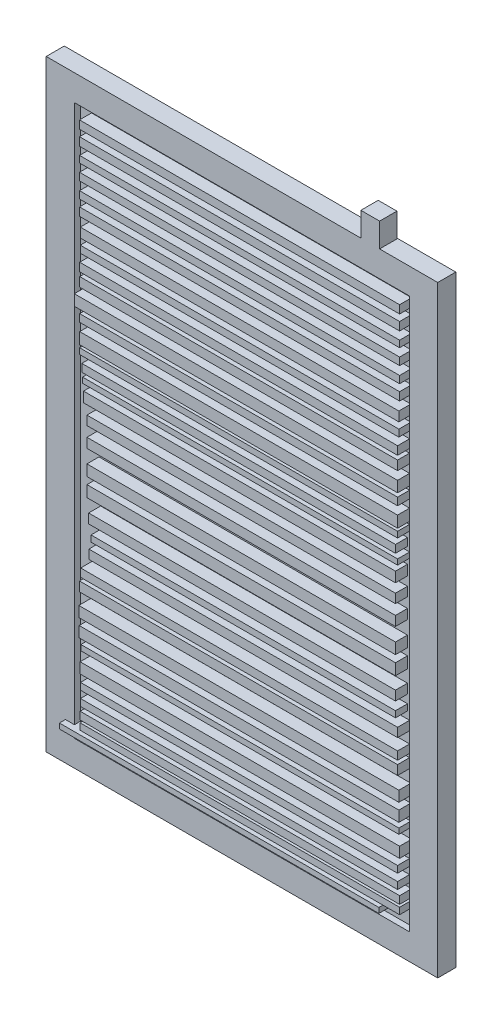
SolidWorks part; units mm, degrees
ref_plane "Front Plane" through (0, 0, 0) normal (0, 0, 1) x (1, 0, 0)
ref_plane "Top Plane" through (0, 0, 0) normal (0, 1, 0) x (1, 0, 0)
ref_plane "Right Plane" through (0, 0, 0) normal (1, 0, 0) x (0, 0, -1)
sketch "Sketch1" plane through (0, 0, 0) normal (0, 0, 1) x (1, 0, 0)
  line L1 (-32.5, 50) -> (32.5, 50)
  line L2 (-32.5, 50) -> (-32.5, -50)
  line L3 (-32.5, -50) -> (32.5, -50)
  line L4 (32.5, 50) -> (32.5, -50)
  point P0 (0, 0)
  point P6 (0, 0)
  dimension "D1" = 65
  dimension "D2" = 100
extrude "Boss-Extrude1" add sketch "Sketch1" along normal blind 3
sketch "Sketch2" plane through (0, 0, 0) normal (0, 0, -1) x (-1, 0, 0)
  line L1 (-27.7051, 45.4905) -> (27.7051, 45.4905)
  line L2 (-27.7051, 45.4905) -> (-27.7051, -45.4905)
  line L3 (-27.7051, -45.4905) -> (27.7051, -45.4905)
  line L4 (27.7051, 45.4905) -> (27.7051, -45.4905)
  line L5 (-27.7051, 45.4905) -> (27.7051, -45.4905) construction
  line L6 (-27.7051, -45.4905) -> (27.7051, 45.4905) construction
  point P0 (0, 0)
extrude "Cut-Extrude1" cut sketch "Sketch2" against normal blind 1
sketch "Sketch3" plane through (0, 0, 3) normal (0, 0, 1) x (1, 0, 0)
  line L1 (-27.8118, 45.7085) -> (27.8118, 45.7085)
  line L2 (-27.8118, 45.7085) -> (-27.8118, -45.7085)
  line L3 (-27.8118, -45.7085) -> (27.8118, -45.7085)
  line L4 (27.8118, 45.7085) -> (27.8118, -45.7085)
  line L5 (-27.8118, 45.7085) -> (27.8118, -45.7085) construction
  line L6 (-27.8118, -45.7085) -> (27.8118, 45.7085) construction
  point P0 (0, 0)
extrude "Cut-Extrude2" cut sketch "Sketch3" against normal blind 1
sketch "Sketch6" plane through (0, 50, 0) normal (0, 1, 0) x (1, 0, 0)
  line L0 (32.5, -3) -> (-32.5, -3) construction
  line L1 (19.7425, -0.1252) -> (22.8506, -0.1252)
  line L2 (19.7425, -0.1252) -> (19.7425, -3)
  line L3 (19.7425, -3) -> (22.8506, -3)
  line L4 (22.8506, -0.1252) -> (22.8506, -3)
  line L5 (19.7425, -0.1252) -> (22.8506, -3) construction
  line L6 (19.7425, -3) -> (22.8506, -0.1252) construction
  point P0 (21.2966, -1.5626)
extrude "Boss-Extrude3" add sketch "Sketch6" along normal blind 4
sketch "Sketch7" plane through (0, 0, 2) normal (0, 0, 1) x (1, 0, 0)
  line L1 (-25.9695, 44.6396) -> (27.1687, 44.6396)
  line L2 (-25.9695, 44.6396) -> (-25.9695, 43.2996)
  line L3 (-25.9695, 43.2996) -> (27.1687, 43.2996)
  line L4 (27.1687, 44.6396) -> (27.1687, 43.2996)
  line L5 (-25.9695, 44.6396) -> (27.1687, 43.2996) construction
  line L6 (-25.9695, 43.2996) -> (27.1687, 44.6396) construction
  line L7 (-25.9695, 42.2223) -> (27.1687, 42.2223)
  line L8 (-25.9695, 42.2223) -> (-25.9695, 40.8553)
  line L9 (-25.9695, 40.8553) -> (27.1687, 40.8553)
  line L10 (27.1687, 42.2223) -> (27.1687, 40.8553)
  line L11 (-25.9695, 42.2223) -> (27.1687, 40.8553) construction
  line L12 (-25.9695, 40.8553) -> (27.1687, 42.2223) construction
  line L13 (-25.9695, 39.5391) -> (27.1687, 39.5391)
  line L14 (-25.9695, 39.5391) -> (-25.9695, 38.446)
  line L15 (-25.9695, 38.446) -> (27.1687, 38.446)
  line L16 (27.1687, 39.5391) -> (27.1687, 38.446)
  line L17 (-25.9695, 39.5391) -> (27.1687, 38.446) construction
  line L18 (-25.9695, 38.446) -> (27.1687, 39.5391) construction
  line L19 (-25.9695, 37.1137) -> (27.1687, 37.1137)
  line L20 (-25.9695, 37.1137) -> (-25.9695, 35.8726)
  line L21 (-25.9695, 35.8726) -> (27.1687, 35.8726)
  line L22 (27.1687, 37.1137) -> (27.1687, 35.8726)
  line L23 (-25.9695, 37.1137) -> (27.1687, 35.8726) construction
  line L24 (-25.9695, 35.8726) -> (27.1687, 37.1137) construction
  line L25 (-25.9695, 34.4668) -> (27.1687, 34.4668)
  line L26 (-25.9695, 34.4668) -> (-25.9695, 33.2688)
  line L27 (-25.9695, 33.2688) -> (27.1687, 33.2688)
  line L28 (27.1687, 34.4668) -> (27.1687, 33.2688)
  line L29 (-25.9695, 34.4668) -> (27.1687, 33.2688) construction
  line L30 (-25.9695, 33.2688) -> (27.1687, 34.4668) construction
  line L31 (-25.9695, 32.1331) -> (27.1687, 32.1331)
  line L32 (-25.9695, 32.1331) -> (-25.9695, 30.7838)
  line L33 (-25.9695, 30.7838) -> (27.1687, 30.7838)
  line L34 (27.1687, 32.1331) -> (27.1687, 30.7838)
  line L35 (-25.9695, 32.1331) -> (27.1687, 30.7838) construction
  line L36 (-25.9695, 30.7838) -> (27.1687, 32.1331) construction
  line L37 (-25.8446, 29.2928) -> (27.0438, 29.2928)
  line L38 (-25.8446, 29.2928) -> (-25.8446, 27.7285)
  line L39 (-25.8446, 27.7285) -> (27.0438, 27.7285)
  line L40 (27.0438, 29.2928) -> (27.0438, 27.7285)
  line L41 (-25.8446, 29.2928) -> (27.0438, 27.7285) construction
  line L42 (-25.8446, 27.7285) -> (27.0438, 29.2928) construction
  line L43 (-25.8446, 25.535) -> (27.0438, 25.535)
  line L44 (-25.8446, 25.535) -> (-25.8446, 26.6899)
  line L45 (-25.8446, 26.6899) -> (27.0438, 26.6899)
  line L46 (27.0438, 25.535) -> (27.0438, 26.6899)
  line L47 (-25.8446, 25.535) -> (27.0438, 26.6899) construction
  line L48 (-25.8446, 26.6899) -> (27.0438, 25.535) construction
  line L49 (-25.9396, 22.8114) -> (26.8318, 22.8114)
  line L50 (-25.9396, 22.8114) -> (-25.9396, 24.1936)
  line L51 (-25.9396, 24.1936) -> (26.8318, 24.1936)
  line L52 (26.8318, 22.8114) -> (26.8318, 24.1936)
  line L53 (-25.9396, 22.8114) -> (26.8318, 24.1936) construction
  line L54 (-25.9396, 24.1936) -> (26.8318, 22.8114) construction
  line L55 (-25.9396, 22.1309) -> (26.8318, 22.1309)
  line L56 (-25.9396, 22.1309) -> (-25.9396, 20.6025)
  line L57 (-25.9396, 20.6025) -> (26.8318, 20.6025)
  line L58 (26.8318, 22.1309) -> (26.8318, 20.6025)
  line L59 (-25.9396, 22.1309) -> (26.8318, 20.6025) construction
  line L60 (-25.9396, 20.6025) -> (26.8318, 22.1309) construction
  line L61 (-26.8318, 17.4202) -> (26.8318, 17.4202)
  line L62 (-26.8318, 17.4202) -> (-26.8318, 19.2207)
  line L63 (-26.8318, 19.2207) -> (26.8318, 19.2207)
  line L64 (26.8318, 17.4202) -> (26.8318, 19.2207)
  line L65 (-26.8318, 17.4202) -> (26.8318, 19.2207) construction
  line L66 (-26.8318, 19.2207) -> (26.8318, 17.4202) construction
  line L67 (-25.9396, 16.8012) -> (26.8318, 16.8012)
  line L68 (-25.9396, 16.8012) -> (-25.9396, 15.5525)
  line L69 (-25.9396, 15.5525) -> (26.8318, 15.5525)
  line L70 (26.8318, 16.8012) -> (26.8318, 15.5525)
  line L71 (-25.9396, 16.8012) -> (26.8318, 15.5525) construction
  line L72 (-25.9396, 15.5525) -> (26.8318, 16.8012) construction
  line L73 (-25.9396, 14.2224) -> (26.8318, 14.2224)
  line L74 (-25.9396, 14.2224) -> (-25.9396, 12.3285)
  line L75 (-25.9396, 12.3285) -> (26.8318, 12.3285)
  line L76 (26.8318, 14.2224) -> (26.8318, 12.3285)
  line L77 (-25.9396, 14.2224) -> (26.8318, 12.3285) construction
  line L78 (-25.9396, 12.3285) -> (26.8318, 14.2224) construction
  line L79 (-25.9396, 11.8938) -> (26.8318, 11.8938)
  line L80 (-25.9396, 11.8938) -> (-25.9396, 10.9204)
  line L81 (-25.9396, 10.9204) -> (26.8318, 10.9204)
  line L82 (26.8318, 11.8938) -> (26.8318, 10.9204)
  line L83 (-25.9396, 11.8938) -> (26.8318, 10.9204) construction
  line L84 (-25.9396, 10.9204) -> (26.8318, 11.8938) construction
  line L85 (-25.5905, 9.8271) -> (26.4827, 9.8271)
  line L86 (-25.5905, 9.8271) -> (-25.5905, 8.5473)
  line L87 (-25.5905, 8.5473) -> (26.4827, 8.5473)
  line L88 (26.4827, 9.8271) -> (26.4827, 8.5473)
  line L89 (-25.5905, 9.8271) -> (26.4827, 8.5473) construction
  line L90 (-25.5905, 8.5473) -> (26.4827, 9.8271) construction
  line L91 (-25.4605, 7.9187) -> (26.8318, 7.9187)
  line L92 (-25.4605, 7.9187) -> (-25.4605, 7.0222)
  line L93 (-25.4605, 7.0222) -> (26.8318, 7.0222)
  line L94 (26.8318, 7.9187) -> (26.8318, 7.0222)
  line L95 (-25.4605, 7.9187) -> (26.8318, 7.0222) construction
  line L96 (-25.4605, 7.0222) -> (26.8318, 7.9187) construction
  line L97 (-25.3048, 5.9832) -> (26.4827, 5.9832)
  line L98 (-25.3048, 5.9832) -> (-25.3048, 4.3035)
  line L99 (-25.3048, 4.3035) -> (26.4827, 4.3035)
  line L100 (26.4827, 5.9832) -> (26.4827, 4.3035)
  line L101 (-25.3048, 5.9832) -> (26.4827, 4.3035) construction
  line L102 (-25.3048, 4.3035) -> (26.4827, 5.9832) construction
  line L103 (-24.7387, 2.8172) -> (26.4827, 2.8172)
  line L104 (-24.7387, 2.8172) -> (-24.7387, 1.3072)
  line L105 (-24.7387, 1.3072) -> (26.4827, 1.3072)
  line L106 (26.4827, 2.8172) -> (26.4827, 1.3072)
  line L107 (-24.7387, 2.8172) -> (26.4827, 1.3072) construction
  line L108 (-24.7387, 1.3072) -> (26.4827, 2.8172) construction
  line L109 (-24.7387, -1.97) -> (26.4827, -1.97)
  line L110 (-24.7387, -1.97) -> (-24.7387, -0.374)
  line L111 (-24.7387, -0.374) -> (26.4827, -0.374)
  line L112 (26.4827, -1.97) -> (26.4827, -0.374)
  line L113 (-24.7387, -1.97) -> (26.4827, -0.374) construction
  line L114 (-24.7387, -0.374) -> (26.4827, -1.97) construction
  line L115 (-24.7387, -4.2007) -> (26.4827, -4.2007)
  line L116 (-24.7387, -4.2007) -> (-24.7387, -6.0222)
  line L117 (-24.7387, -6.0222) -> (26.4827, -6.0222)
  line L118 (26.4827, -4.2007) -> (26.4827, -6.0222)
  line L119 (-24.7387, -4.2007) -> (26.4827, -6.0222) construction
  line L120 (-24.7387, -6.0222) -> (26.4827, -4.2007) construction
  line L121 (-24.7387, -7.1812) -> (26.4827, -7.1812)
  line L122 (-24.7387, -7.1812) -> (-24.7387, -9.0562)
  line L123 (-24.7387, -9.0562) -> (26.4827, -9.0562)
  line L124 (26.4827, -7.1812) -> (26.4827, -9.0562)
  line L125 (-24.7387, -7.1812) -> (26.4827, -9.0562) construction
  line L126 (-24.7387, -9.0562) -> (26.4827, -7.1812) construction
  line L127 (-24.4615, -12.6899) -> (26.4827, -12.6899)
  line L128 (-24.4615, -12.6899) -> (-24.4615, -11.1187)
  line L129 (-24.4615, -11.1187) -> (26.4827, -11.1187)
  line L130 (26.4827, -12.6899) -> (26.4827, -11.1187)
  line L131 (-24.4615, -12.6899) -> (26.4827, -11.1187) construction
  line L132 (-24.4615, -11.1187) -> (26.4827, -12.6899) construction
  line L133 (-24.0643, -14.0775) -> (26.4827, -14.0775)
  line L134 (-24.0643, -14.0775) -> (-24.0643, -15.1104)
  line L135 (-24.0643, -15.1104) -> (26.4827, -15.1104)
  line L136 (26.4827, -14.0775) -> (26.4827, -15.1104)
  line L137 (-24.0643, -14.0775) -> (26.4827, -15.1104) construction
  line L138 (-24.0643, -15.1104) -> (26.4827, -14.0775) construction
  line L139 (-24.4134, -16.2836) -> (26.8318, -16.2836)
  line L140 (-24.4134, -16.2836) -> (-24.4134, -17.7752)
  line L141 (-24.4134, -17.7752) -> (26.8318, -17.7752)
  line L142 (26.8318, -16.2836) -> (26.8318, -17.7752)
  line L143 (-24.4134, -16.2836) -> (26.8318, -17.7752) construction
  line L144 (-24.4134, -17.7752) -> (26.8318, -16.2836) construction
  line L145 (-25.7787, -21.0328) -> (26.8318, -21.0328)
  line L146 (-25.7787, -21.0328) -> (-25.7787, -19.6864)
  line L147 (-25.7787, -19.6864) -> (26.8318, -19.6864)
  line L148 (26.8318, -21.0328) -> (26.8318, -19.6864)
  line L149 (-25.7787, -21.0328) -> (26.8318, -19.6864) construction
  line L150 (-25.7787, -19.6864) -> (26.8318, -21.0328) construction
  line L151 (-25.9733, -21.6532) -> (26.8318, -21.6532)
  line L152 (-25.9733, -21.6532) -> (-25.9733, -23.2193)
  line L153 (-25.9733, -23.2193) -> (26.8318, -23.2193)
  line L154 (26.8318, -21.6532) -> (26.8318, -23.2193)
  line L155 (-25.9733, -21.6532) -> (26.8318, -23.2193) construction
  line L156 (-25.9733, -23.2193) -> (26.8318, -21.6532) construction
  line L157 (-26.0897, -26.9694) -> (27.0438, -26.9694)
  line L158 (-26.0897, -26.9694) -> (-26.0897, -25.2245)
  line L159 (-26.0897, -25.2245) -> (27.0438, -25.2245)
  line L160 (27.0438, -26.9694) -> (27.0438, -25.2245)
  line L161 (-26.0897, -26.9694) -> (27.0438, -25.2245) construction
  line L162 (-26.0897, -25.2245) -> (27.0438, -26.9694) construction
  line L163 (-26.0271, -29.854) -> (27.0438, -29.854)
  line L164 (-26.0271, -29.854) -> (-26.0271, -28.0846)
  line L165 (-26.0271, -28.0846) -> (27.0438, -28.0846)
  line L166 (27.0438, -29.854) -> (27.0438, -28.0846)
  line L167 (-26.0271, -29.854) -> (27.0438, -28.0846) construction
  line L168 (-26.0271, -28.0846) -> (27.0438, -29.854) construction
  line L169 (-25.7401, -30.6675) -> (27.0438, -30.6675)
  line L170 (-25.7401, -30.6675) -> (-25.7401, -31.577)
  line L171 (-25.7401, -31.577) -> (27.0438, -31.577)
  line L172 (27.0438, -30.6675) -> (27.0438, -31.577)
  line L173 (-25.7401, -30.6675) -> (27.0438, -31.577) construction
  line L174 (-25.7401, -31.577) -> (27.0438, -30.6675) construction
  line L175 (-25.865, -33.2131) -> (27.1687, -33.2131)
  line L176 (-25.865, -33.2131) -> (-25.865, -34.9736)
  line L177 (-25.865, -34.9736) -> (27.1687, -34.9736)
  line L178 (27.1687, -33.2131) -> (27.1687, -34.9736)
  line L179 (-25.865, -33.2131) -> (27.1687, -34.9736) construction
  line L180 (-25.865, -34.9736) -> (27.1687, -33.2131) construction
  line L181 (-25.8151, -36.153) -> (26.8318, -36.153)
  line L182 (-25.8151, -36.153) -> (-25.8151, -37.2777)
  line L183 (-25.8151, -37.2777) -> (26.8318, -37.2777)
  line L184 (26.8318, -36.153) -> (26.8318, -37.2777)
  line L185 (-25.8151, -36.153) -> (26.8318, -37.2777) construction
  line L186 (-25.8151, -37.2777) -> (26.8318, -36.153) construction
  line L187 (-25.8151, -38.4676) -> (26.8318, -38.4676)
  line L188 (-25.8151, -38.4676) -> (-25.8151, -39.6143)
  line L189 (-25.8151, -39.6143) -> (26.8318, -39.6143)
  line L190 (26.8318, -38.4676) -> (26.8318, -39.6143)
  line L191 (-25.8151, -38.4676) -> (26.8318, -39.6143) construction
  line L192 (-25.8151, -39.6143) -> (26.8318, -38.4676) construction
  line L193 (-25.865, -40.3272) -> (27.1687, -40.3272)
  line L194 (-25.865, -40.3272) -> (-25.865, -41.5829)
  line L195 (-25.865, -41.5829) -> (27.1687, -41.5829)
  line L196 (27.1687, -40.3272) -> (27.1687, -41.5829)
  line L197 (-25.865, -40.3272) -> (27.1687, -41.5829) construction
  line L198 (-25.865, -41.5829) -> (27.1687, -40.3272) construction
  line L199 (-25.865, -41.995) -> (27.1687, -41.995)
  line L200 (-25.865, -41.995) -> (-25.865, -43.07)
  line L201 (-25.865, -43.07) -> (27.1687, -43.07)
  line L202 (27.1687, -41.995) -> (27.1687, -43.07)
  line L203 (-25.865, -41.995) -> (27.1687, -43.07) construction
  line L204 (-25.865, -43.07) -> (27.1687, -41.995) construction
  line L205 (-29.3074, -43.7424) -> (23.7263, -43.7424)
  line L206 (-29.3074, -43.7424) -> (-29.3074, -44.6022)
  line L207 (-29.3074, -44.6022) -> (23.7263, -44.6022)
  line L208 (23.7263, -43.7424) -> (23.7263, -44.6022)
  line L209 (-29.3074, -43.7424) -> (23.7263, -44.6022) construction
  line L210 (-29.3074, -44.6022) -> (23.7263, -43.7424) construction
  point P0 (0.5996, 43.9696)
  point P5 (0.5996, 38.9925)
  point P7 (0.5996, 41.5388)
  point P15 (0.5996, 36.4931)
  point P20 (0.5996, 33.8678)
  point P25 (0.5996, 31.4584)
  point P30 (0.5996, 28.5106)
  point P35 (0.5996, 26.1124)
  point P40 (0.4461, 21.3667)
  point P41 (0.4461, 23.5025)
  point P50 (0, 18.3205)
  point P55 (0.4461, 16.1769)
  point P60 (0.4461, 13.2755)
  point P65 (0.4461, 11.4071)
  point P70 (0.4461, 9.1872)
  point P75 (0.6856, 7.4704)
  point P80 (0.5889, 5.1433)
  point P85 (0.872, 2.0622)
  point P90 (0.872, -1.172)
  point P95 (0.872, -5.1114)
  point P100 (0.872, -8.1187)
  point P105 (1.0106, -11.9043)
  point P110 (1.2092, -14.594)
  point P115 (1.2092, -17.0294)
  point P120 (0.5266, -20.3596)
  point P125 (0.4293, -22.4362)
  point P130 (0.477, -26.0969)
  point P135 (0.5083, -28.9693)
  point P140 (0.6518, -31.1223)
  point P145 (0.6518, -34.0934)
  point P150 (0.5083, -36.7153)
  point P155 (0.5083, -39.041)
  point P160 (0.6518, -40.955)
  point P165 (0.6518, -42.5325)
  point P170 (-2.7905, -44.1723)
extrude "Boss-Extrude4" add sketch "Sketch7" along normal blind 2
